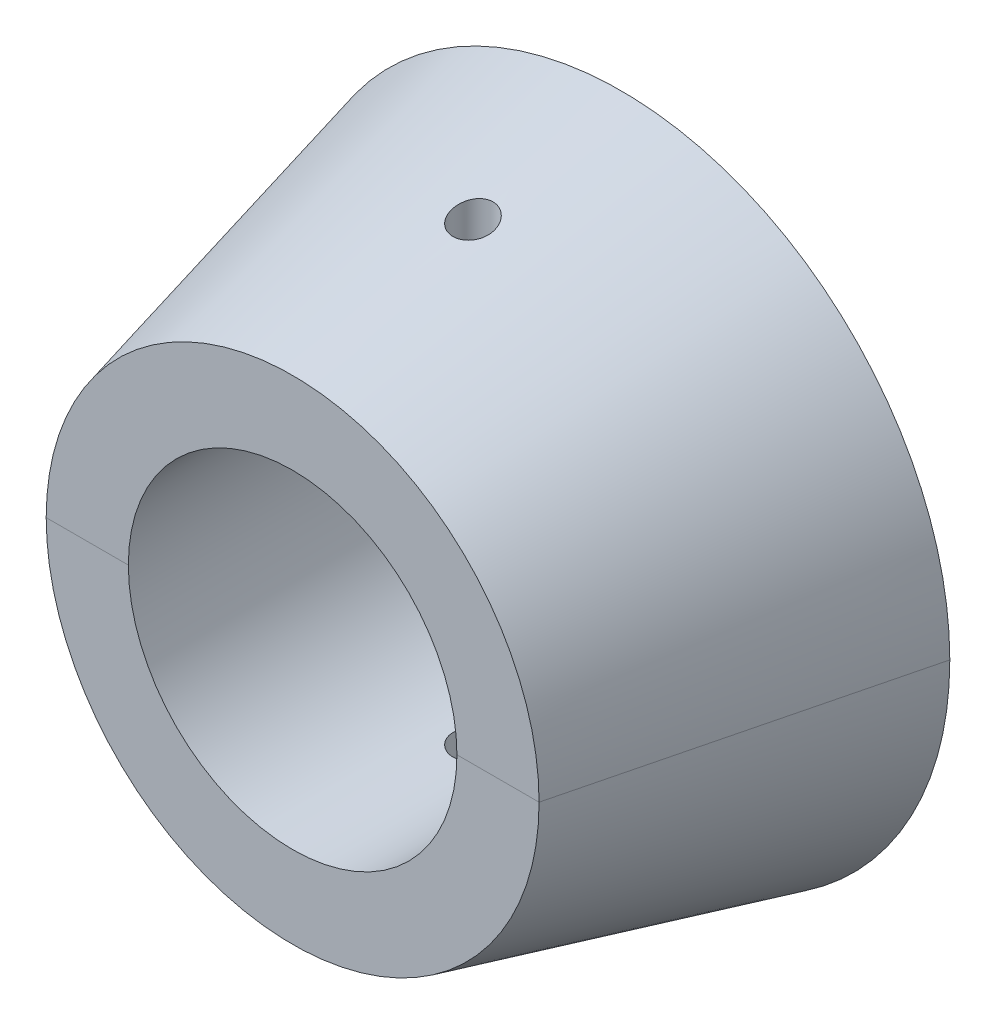
SolidWorks part; units mm, degrees
ref_plane "Front Plane" through (0, 0, 0) normal (0, 0, 1) x (1, 0, 0)
ref_plane "Top Plane" through (0, 0, 0) normal (0, 1, 0) x (1, 0, 0)
ref_plane "Right Plane" through (0, 0, 0) normal (1, 0, 0) x (0, 0, -1)
sketch "Sketch1" plane through (0, 0, 0) normal (0, 0, 1) x (1, 0, 0)
  circle A0 centre (0, 0) radius 12.5
  dimension "D1" = 25
extrude "Boss-Extrude1" add sketch "Sketch1" along normal blind 5
sketch "Sketch3" plane through (0, 0, 0) normal (0, 1, 0) x (1, 0, 0)
  line L0 (0, -5) -> (-20, -5)
  line L1 (0, -5) -> (0, -25)
  line L2 (0, -25) -> (-15, -25)
  line L3 (-15, -25) -> (-20, -5)
  line L4 (-12.5, -5) -> (12.5, -5) construction
  dimension "D1" = 20
  dimension "D2" = 20
  dimension "D3" = 15
  dimension "D4" = 0
sweep "Sweep1" add profiles "Sketch3" path edge at (12.5, 0, 5)
sketch "Sketch4" plane through (0, 0, 25) normal (0, 0, 1) x (1, 0, 0)
  circle A0 centre (0, 0) radius 10
extrude "Cut-Extrude1" cut sketch "Sketch4" against normal blind 20
sketch "Sketch11" plane through (0, 0, 0) normal (0, 1, 0) x (1, 0, 0)
  line L0 (20, -5) -> (-20, -5) construction
  line L1 (-3, -10) -> (3, -10)
  line L2 (-3, -10) -> (-3, -14)
  line L4 (3, -10) -> (3, -14)
  line L5 (0, 0) -> (0, -10) construction
  line L6 (12.5, 0) -> (-12.5, 0) construction
  line L7 (-15, -25) -> (15, -25) construction
  line L8 (0, -21) -> (0, -25) construction
  arc A3 (-3, -14) -> (3, -14) centre (0, -14) ccw
  dimension "D1" = 5
  dimension "D3" = 6
  dimension "D4" = 3
extrude "Cut-Extrude2" cut sketch "Sketch11" against normal blind 5 from offset 16.25 contours L4 A3 L2 L1 offset against normal yes
hole_wizard "CSK for #2 Flat Head Machine Screw (100)2" positions "3DSketch4" profile "Sketch13" countersink size "#2" standard "ANSI Inch" end condition through all
sketch3d "3DSketch4"
  point P0 (0, -16.25, 14.0233)
sketch "Sketch13" plane through (0, -16.25, 14.0233) normal (1, 0, 0) x (0, 0, -1)
  line L0 (0, 0) -> (0, 36.25)
  line L1 (0, 36.25) -> (1.2192, 36.25)
  line L2 (1.2192, 36.25) -> (1.2192, 0.8099)
  line L3 (1.2192, 0.8099) -> (2.1844, 0)
  line L5 (2.1844, 0) -> (0, 0)
  line L6 (-1.2192, 0.8099) -> (-2.1844, 0) construction
  line L11 (0, -6.35) -> (0, 107.95) construction
  dimension "Thru Hole Dia." = 2.4384
  dimension "Thru Hole Depth" = 36.25
  dimension "Near C'Sink Dia." = 4.3688
  dimension "Near C'Sink Angle" = 100
